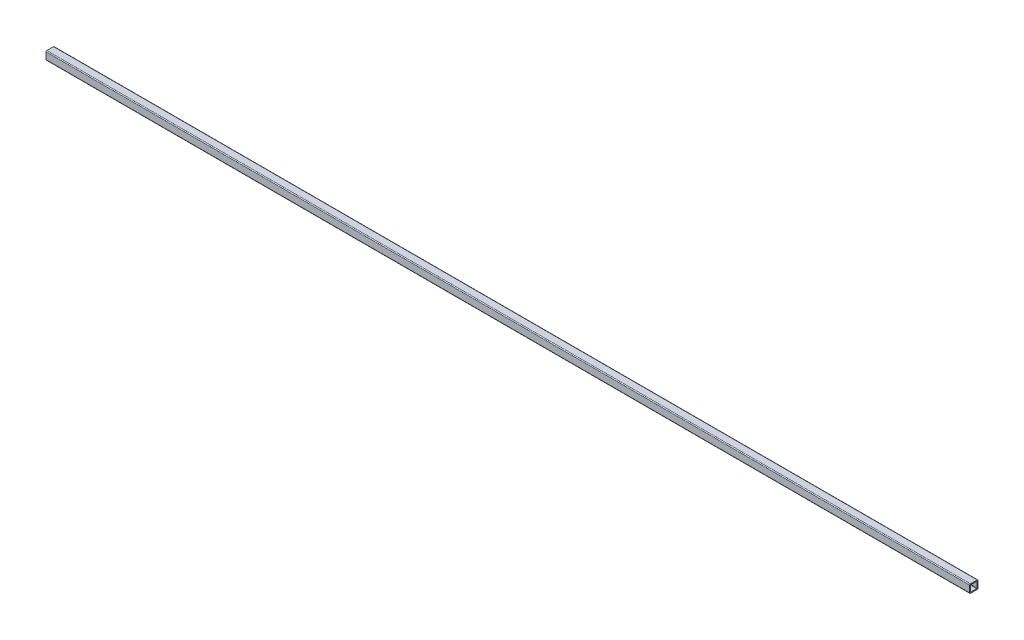
SolidWorks part; units mm, degrees
ref_plane "Front Plane" through (0, 0, 0) normal (0, 0, 1) x (1, 0, 0)
ref_plane "Top Plane" through (0, 0, 0) normal (0, 1, 0) x (1, 0, 0)
ref_plane "Right Plane" through (0, 0, 0) normal (1, 0, 0) x (0, 0, -1)
sketch "Sketch3" plane through (0, 0, 0) normal (1, 0, 0) x (0, 0, -1)
  line L1 (-12.7, 12.7) -> (12.7, 12.7)
  line L2 (-12.7, 12.7) -> (-12.7, -12.7)
  line L3 (-12.7, -12.7) -> (12.7, -12.7)
  line L4 (12.7, 12.7) -> (12.7, -12.7)
  line L5 (-12.7, 12.7) -> (12.7, -12.7) construction
  line L6 (-12.7, -12.7) -> (12.7, 12.7) construction
  line L7 (-9.652, -9.652) -> (9.652, -9.652)
  line L8 (-9.652, -9.652) -> (-9.652, 9.652)
  line L9 (-9.652, 9.652) -> (9.652, 9.652)
  line L10 (9.652, -9.652) -> (9.652, 9.652)
  line L11 (-9.652, -9.652) -> (9.652, 9.652) construction
  line L12 (-9.652, 9.652) -> (9.652, -9.652) construction
  point P0 (0, 0)
  point P6 (0, 0)
  dimension "D1" = 25.4
  dimension "D2" = 19.304
  dimension "D3" = 19.304
  dimension "D4" = 25.4
extrude "Boss-Extrude1" add sketch "Sketch3" against normal blind 2830
fillet "Fillet1" radius 2.5 4 edges at (-1415, -12.7, -12.7) (-1415, -12.7, 12.7) (-1415, 12.7, -12.7) (-1415, 12.7, 12.7)
fillet "Fillet2" radius 1 4 edges at (-1415, -9.652, -9.652) (-1415, 9.652, -9.652) (-1415, 9.652, 9.652) (-1415, -9.652, 9.652)
